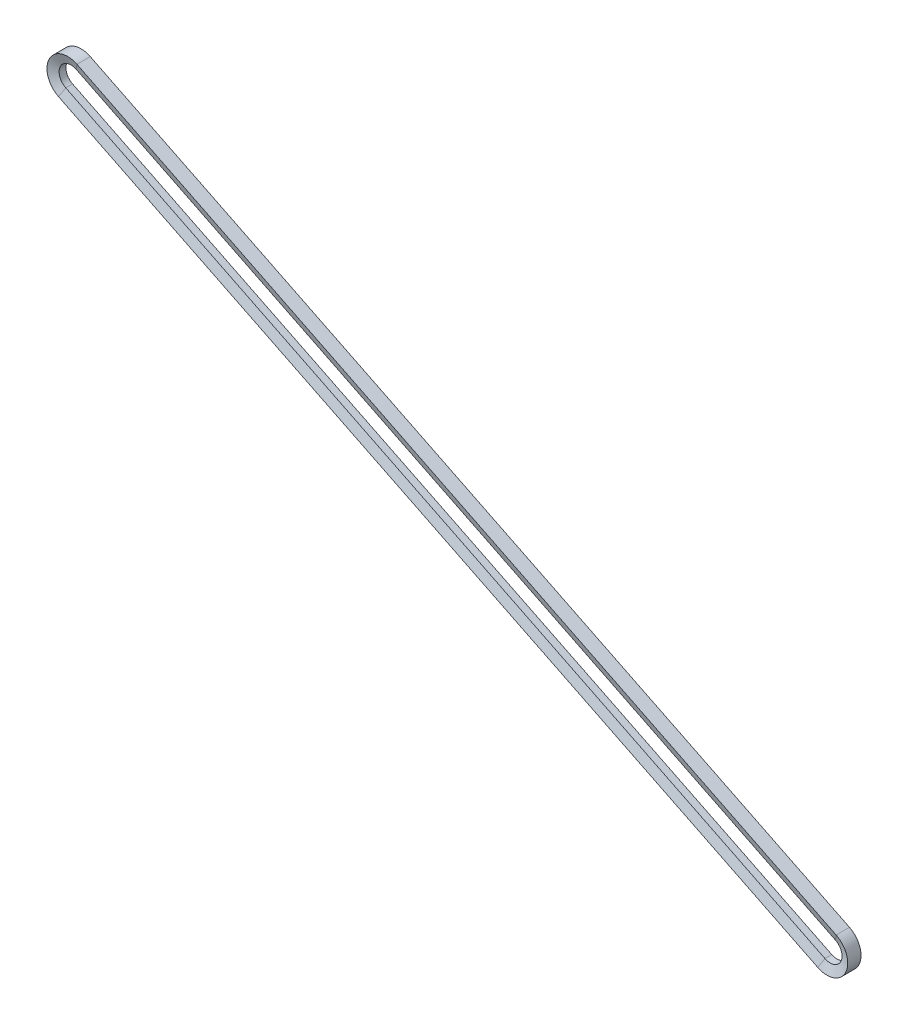
SolidWorks part; units mm, degrees
ref_plane "前视基准面" through (0, 0, 0) normal (0, 0, 1) x (1, 0, 0)
ref_plane "上视基准面" through (0, 0, 0) normal (0, 1, 0) x (1, 0, 0)
ref_plane "右视基准面" through (0, 0, 0) normal (1, 0, 0) x (0, 0, -1)
sketch "草图2" plane through (0, 0, 0) normal (0, 0, 1) x (1, 0, 0)
  line L0 (0, 0) -> (1, 0) construction
  line L1 (0, 0) -> (0, 1) construction
  line L2 (2.3443, 4.7533) -> (342.1178, -162.8213)
  line L3 (337.4292, -172.328) -> (-2.3443, -4.7533)
  arc A0 (-2.3443, -4.7533) -> (2.3443, 4.7533) centre (0, 0) cw
  arc A1 (342.1178, -162.8213) -> (337.4292, -172.328) centre (339.7735, -167.5747) cw
ref_plane "基准面4" through (0, 0, 0) normal (0.8969, -0.4423, 0) x (0, 0, -1)
sketch "草图3" plane through (0, 0, 0) normal (0.8969, -0.4423, 0) x (0, 0, -1)
  line L0 (-1.525, 5.3) -> (1.525, 5.3)
  line L1 (0, 5.3) -> (0, -5.3) construction
  line L2 (0, 5.3) -> (0, -5.3) construction
  line L3 (1.525, 5.3) -> (2.9809, 9.3)
  line L4 (0, 5.3) -> (0, 9.3)
  line L8 (-2.9809, 9.3) -> (2.9809, 9.3)
  line L9 (-1.525, 5.3) -> (-2.9809, 9.3)
  dimension "D1" = 110
sweep "扫描1" add profiles "草图3" path "草图2"
